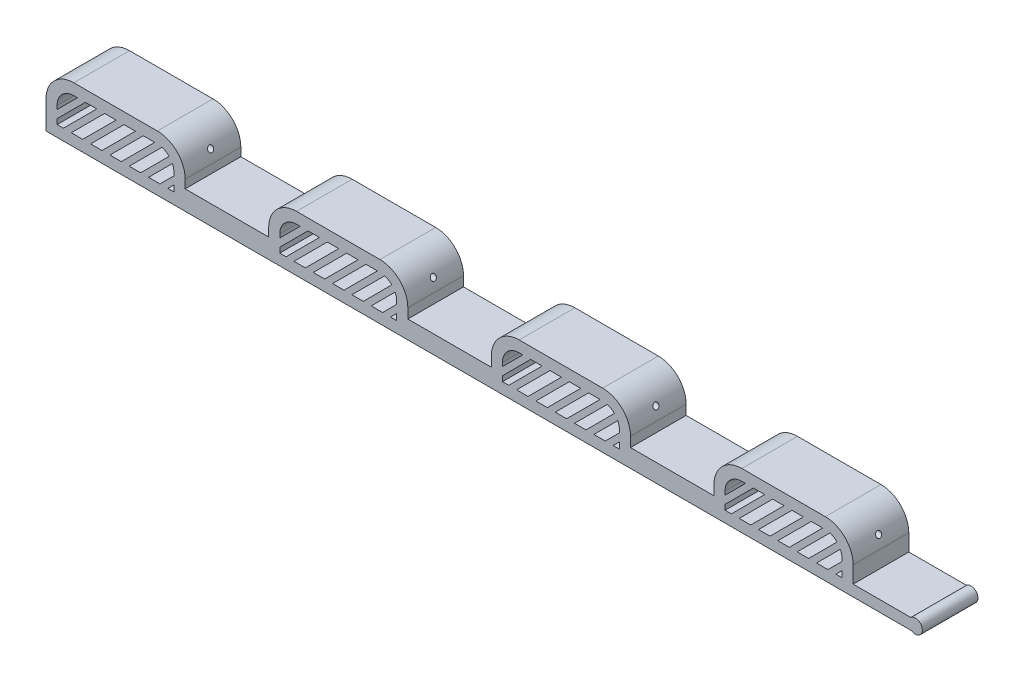
SolidWorks part; units mm, degrees
material "Rubber"
ref_plane "Front Plane" through (0, 0, 0) normal (0, 0, 1) x (1, 0, 0)
ref_plane "Top Plane" through (0, 0, 0) normal (0, 1, 0) x (1, 0, 0)
ref_plane "Right Plane" through (0, 0, 0) normal (1, 0, 0) x (0, 0, -1)
sketch "Sketch1" plane through (0, 0, 0) normal (0, 0, 1) x (1, 0, 0)
  line L14 (55, 0) -> (-55, 0) construction
  line L15 (0, 0) -> (25, 0)
  line L16 (0, 0) -> (0, 10)
  line L17 (0, 10) -> (25, 10)
  line L18 (25, 0) -> (25, 10)
  line L19 (25, 2) -> (40, 2)
  line L20 (25, 2) -> (25, 0)
  line L21 (25, 0) -> (40, 0)
  line L22 (40, 2) -> (40, 0)
  line L23 (40, 0) -> (40, 10)
  line L24 (40, 0) -> (65, 0)
  line L25 (65, 0) -> (65, 10)
  line L26 (40, 10) -> (65, 10)
  line L27 (65, 2) -> (65, 0)
  line L28 (65, 2) -> (80, 2)
  line L29 (80, 2) -> (80, 0)
  line L30 (65, 0) -> (80, 0)
  line L31 (80, 0) -> (80, 10)
  line L32 (80, 0) -> (105, 0)
  line L33 (105, 0) -> (105, 10)
  line L34 (80, 10) -> (105, 10)
  line L35 (105, 2) -> (105, 0)
  line L36 (105, 2) -> (120, 2)
  line L37 (120, 2) -> (120, 0)
  line L38 (105, 0) -> (120, 0)
  line L39 (120, 0) -> (120, 10)
  line L40 (120, 0) -> (145, 0)
  line L41 (145, 0) -> (145, 10)
  line L42 (120, 10) -> (145, 10)
  line L43 (145, 2) -> (145, 0)
  line L44 (145, 2) -> (157, 2)
  line L46 (145, 0) -> (155.5117, 0)
  line L47 (160, 2) -> (160, 0) [skipped]
  circle A0 centre (156.1807, 1.0559) radius 1.25
  point P30 (40, 1)
  dimension "D6" = 0
  dimension "D8" = 2.5
  dimension "D1" = 25
  dimension "D2" = 10
  dimension "D3" = 15
  dimension "D4" = 2
  dimension "D7" = 12
  dimension "D5" = 4
extrude "Boss-Extrude1" add sketch "Sketch1" along normal blind 10 contours L22 L19 L18 L21 | L26 L23 L22 L24 L25 | L25 L30 L29 L28 | L34 L31 L29 L32 L33 | L33 L38 L37 L36 | L42 L39 L37 L40 L41 | A0 L44 L41 L46 | A0
fillet "Fillet1" radius 5 8 edges at (0, 10, 5) (25, 10, 5) (40, 10, 5) (65, 10, 5) (80, 10, 5) (105, 10, 5) (120, 10, 5) (145, 10, 5)
sketch "Sketch4" plane through (0, 0, 10) normal (0, 0, 1) x (1, 0, 0)
  line L0 (23, 5) -> (23, 2)
  line L1 (23, 2) -> (2, 2)
  line L2 (2, 2) -> (2, 5)
  line L3 (5, 8) -> (20, 8)
  line L4 (-0.7167, 1.6268) -> (10.125, 12.4686)
  line L5 (55, 0) -> (-55, 0) construction
  line L6 (0.6975, 1.6268) -> (12.4123, 13.3416)
  line L8 (2.7523, 1.6268) -> (13.5941, 12.4686)
  line L9 (4.1665, 1.6268) -> (15.8813, 13.3416)
  line L10 (6.2213, 1.6268) -> (17.0631, 12.4686)
  line L11 (7.6356, 1.6268) -> (19.3504, 13.3416)
  line L12 (9.6904, 1.6268) -> (20.5321, 12.4686)
  line L13 (11.1046, 1.6268) -> (22.8194, 13.3416)
  line L14 (13.1594, 1.6268) -> (24.0012, 12.4686)
  line L15 (14.5736, 1.6268) -> (26.2884, 13.3416)
  line L16 (16.6284, 1.6268) -> (27.4702, 12.4686)
  line L18 (18.0426, 1.6268) -> (29.7574, 13.3416)
  line L19 (20.0975, 1.6268) -> (30.9392, 12.4686)
  line L20 (21.5117, 1.6268) -> (33.2265, 13.3416)
  line L42 (63, 5) -> (63, 2)
  line L43 (45, 8) -> (60, 8)
  line L44 (42, 2) -> (42, 5)
  line L45 (63, 5) -> (63, 2)
  line L46 (45, 8) -> (60, 8)
  line L47 (42, 2) -> (42, 5)
  line L51 (85, 8) -> (100, 8)
  line L52 (82, 2) -> (82, 5)
  line L53 (85, 8) -> (100, 8)
  line L54 (82, 2) -> (82, 5)
  line L68 (103, 2) -> (103, 5)
  line L69 (103, 2) -> (103, 5)
  line L78 (143, 2) -> (122, 2)
  line L79 (103, 2) -> (82, 2)
  line L80 (63, 2) -> (42, 2)
  line L81 (143, 5) -> (143, 2)
  line L82 (125, 8) -> (140, 8)
  line L83 (122, 2) -> (122, 5)
  line L84 (143, 5) -> (143, 2)
  line L85 (125, 8) -> (140, 8)
  line L86 (122, 2) -> (122, 5)
  arc A0 (5, 8) -> (2, 5) centre (5, 5) ccw
  arc A1 (23, 5) -> (20, 8) centre (20, 5) ccw
  arc A27 (63, 5) -> (60, 8) centre (60, 5) ccw
  arc A28 (45, 8) -> (42, 5) centre (45, 5) ccw
  arc A29 (63, 5) -> (60, 8) centre (60, 5) ccw
  arc A30 (45, 8) -> (42, 5) centre (45, 5) ccw
  arc A32 (85, 8) -> (82, 5) centre (85, 5) ccw
  arc A33 (85, 8) -> (82, 5) centre (85, 5) ccw
  arc A45 (103, 5) -> (100, 8) centre (100, 5) ccw
  arc A46 (103, 5) -> (100, 8) centre (100, 5) ccw
  arc A54 (143, 5) -> (140, 8) centre (140, 5) ccw
  arc A55 (125, 8) -> (122, 5) centre (125, 5) ccw
  arc A56 (143, 5) -> (140, 8) centre (140, 5) ccw
  arc A57 (125, 8) -> (122, 5) centre (125, 5) ccw
  dimension "D6" = 45
  dimension "D7" = 1
  dimension "D1" = 2
  dimension "D2" = 2
  dimension "D3" = 2
  dimension "D4" = 2
  dimension "D5" = 2
  dimension "D8" = 7
extrude "Cut-Extrude1" cut sketch "Sketch4" against normal blind 10 contours L3 A0 L2 L4 | L1 L8 L3 L6 L2 | L1 L10 L3 L9 | L1 L12 L3 L11 | L1 L14 L3 L13 | L16 A1 L15 L1 | L0 A1 L18 L1 L19 | L20 L1 L0
pattern_linear "LPattern1" count 4 spacing 40 along (1, 0, 0) of "Cut-Extrude1"
sketch "Sketch5" plane through (0, 0, 0) normal (1, 0, 0) x (0, 0, -1)
  line L0 (-5, 10) -> (-5, 0.9791)
  line L1 (-10, 10) -> (0, 10) construction
  circle A0 centre (-5, 7) radius 0.5
  dimension "D2" = 1
  dimension "D1" = 3
extrude "Cut-Extrude2" cut sketch "Sketch5" against normal through all both and the other way through all contours L0 A0 | L0 A0
sketch "Sketch6" plane through (0, 10, 0) normal (0, 1, 0) x (1, 0, 0)
  line L0 (-55, 0) -> (55, 0) construction
  line L1 (7.5, 0) -> (17.5, 0)
  line L2 (7.5, 0) -> (7.5, -10)
  line L3 (7.5, -10) -> (17.5, -10)
  line L4 (17.5, 0) -> (17.5, -10)
  line L5 (5, -10) -> (20, -10) construction
  line L6 (5, 0) -> (5, -10) construction
  dimension "D1" = 2.5
  dimension "D2" = 10
extrude "Cut-Extrude3" [suppressed] cut sketch "Sketch6" against normal blind 0.5
pattern_linear "LPattern2" [suppressed] count 4 spacing 40
sketch "Sketch7" plane through (0, 0, 0) normal (0, 0, 1) x (1, 0, 0)
  line L0 (25, 2) -> (25, 5) construction
  line L1 (25, 3.5) -> (40, 3.5)
  line L2 (25, 3.5) -> (25, 2)
  line L3 (25, 2) -> (40, 2)
  line L4 (40, 3.5) -> (40, 2)
  line L5 (65, 2) -> (65, 5) construction
  line L6 (65, 3.25) -> (80, 3.25)
  line L7 (65, 3.25) -> (65, 2)
  line L8 (65, 2) -> (80, 2)
  line L9 (80, 3.25) -> (80, 2)
  line L10 (105, 2) -> (105, 5) construction
  line L11 (105, 3.25) -> (120, 3.25)
  line L12 (105, 3.25) -> (105, 2)
  line L13 (105, 2) -> (120, 2)
  line L14 (120, 3.25) -> (120, 2)
  dimension "D1" = 1.5
  dimension "D2" = 1.25
  dimension "D3" = 1.25
extrude "Boss-Extrude2" add sketch "Sketch7" along normal up to surface (10 mm away) up to face at (98.7372, 4.7714, 10)
